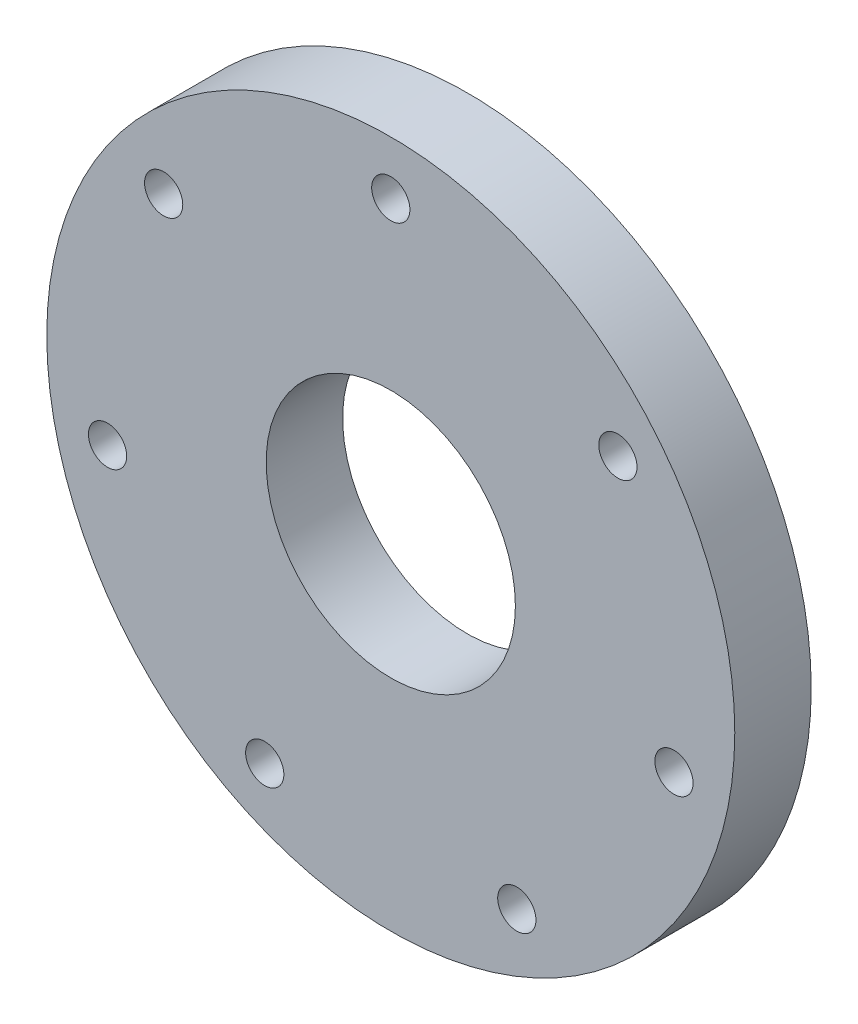
SolidWorks part; units mm, degrees
ref_plane "Front Plane" through (0, 0, 0) normal (0, 0, 1) x (1, 0, 0)
ref_plane "Top Plane" through (0, 0, 0) normal (0, 1, 0) x (1, 0, 0)
ref_plane "Right Plane" through (0, 0, 0) normal (1, 0, 0) x (0, 0, -1)
sketch "Sketch1" plane through (0, 0, 0) normal (0, 0, 1) x (1, 0, 0)
  line L0 (0, 0) -> (0, 19) construction
  circle A0 centre (0, 0) radius 22.5
  circle A1 centre (0, 0) radius 19 construction
  circle A2 centre (0, 19) radius 1.25
  circle A3 centre (14.8548, 11.8463) radius 1.25
  circle A4 centre (18.5236, -4.2279) radius 1.25
  circle A5 centre (8.2438, -17.1184) radius 1.25
  circle A6 centre (-8.2438, -17.1184) radius 1.25
  circle A7 centre (-18.5236, -4.2279) radius 1.25
  circle A8 centre (0, 0) radius 8.15
  circle A9 centre (-14.8548, 11.8463) radius 1.25
  point P19 (0, 0)
  dimension "D1" = 38
  dimension "D2" = 45
  dimension "D3" = 2.5
  dimension "D5" = 16.3
  dimension "D4" = 7
extrude "Boss-Extrude1" add sketch "Sketch1" along normal blind 5
